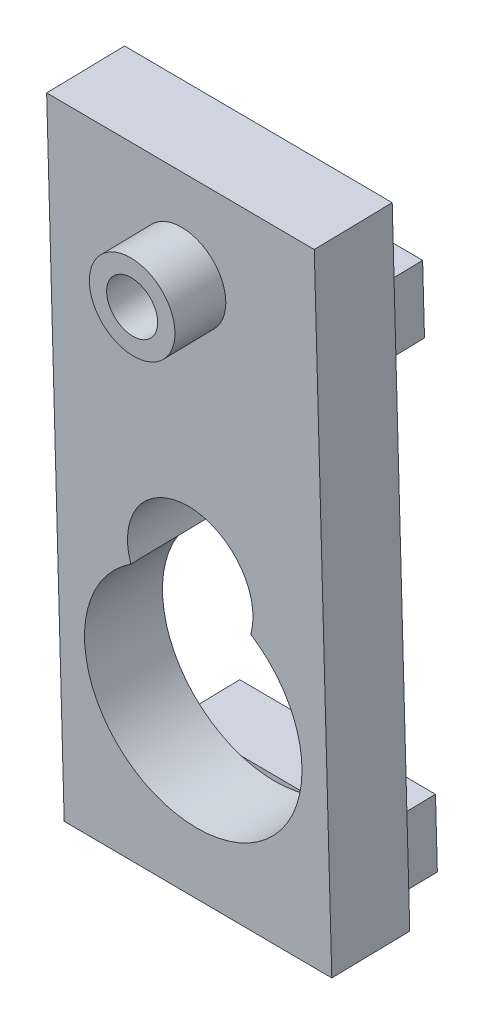
SolidWorks part; units mm, degrees
ref_plane "前视基准面" through (0, 0, 0) normal (0, 0, 1) x (1, 0, 0)
ref_plane "上视基准面" through (0, 0, 0) normal (0, 1, 0) x (1, 0, 0)
ref_plane "右视基准面" through (0, 0, 0) normal (1, 0, 0) x (0, 0, -1)
other "Configuration Table"
sketch "草图1" plane through (-0.7359, -2.9845, 108.8258) normal (-0.0068, -0.0274, 0.9996) x (1, -0.0002, 0.0068)
  line L0 (-20.1179, -7.5053) -> (-4.1179, -7.5053)
  line L1 (-4.1179, -7.5053) -> (-4.1179, 30.4947)
  line L2 (-4.1179, 30.4947) -> (-20.1179, 30.4947)
  line L3 (-20.1179, 30.4947) -> (-20.1179, -7.5053)
  dimension "D1" = 38
  dimension "D2" = 16
  dimension "D3" = 90
extrude "凸台-拉伸1" add sketch "草图1" along normal blind 4.6
sketch "草图5" plane through (-0.7359, -2.9845, 108.8258) normal (0.0068, 0.0274, -0.9996) x (-1, 0.0002, -0.0068)
  line L1 (20.1179, 30.4947) -> (20.1179, -7.5053) construction
  arc A2 (15.7034, 8.1663) -> (8.5324, 8.1663) centre (12.1179, 9.2647) ccw
  arc A3 (8.5324, 8.1663) -> (15.7034, 8.1663) centre (12.1179, 2.7447) ccw
  dimension "D1" = 8
extrude "切除-拉伸3" cut sketch "草图5" against normal up to next
sketch "草图6" plane through (-0.7359, -2.9845, 108.8258) normal (0.0068, 0.0274, -0.9996) x (-1, 0.0002, -0.0068)
  line L0 (6.2679, 20.3447) -> (6.2679, 24.3947)
  line L1 (6.2679, 24.3947) -> (17.9679, 24.3947)
  line L2 (17.9679, 24.3947) -> (17.9679, 20.3447)
  line L3 (17.5762, 23.5172) -> (17.9679, 20.3447) construction
  line L4 (17.9679, 20.3447) -> (6.2679, 20.3447)
  line L5 (7.2679, -3.4553) -> (17.9679, -3.4553)
  line L6 (17.9679, -3.4553) -> (17.9679, -7.5053)
  line L7 (20.1179, -7.5053) -> (4.1179, -7.5053) construction
  line L8 (17.9679, -7.5053) -> (6.2679, -7.5053)
  line L9 (6.2679, -7.5053) -> (6.2679, -3.4553)
  line L10 (6.2679, -3.4553) -> (7.2679, -3.4553)
  line L11 (6.2679, -2.4553) -> (6.2679, -3.4553) construction
  circle A0 centre (12.1179, 21.9447) radius 1
  circle A1 centre (12.1179, -5.0553) radius 1
extrude "凸台-拉伸2" add sketch "草图6" along normal up to surface (3.75 mm away)
sketch "草图9" plane through (-0.767, -3.1106, 113.424) normal (-0.0068, -0.0274, 0.9996) x (1, -0.0002, 0.0068)
  line L1 (-12.1179, 2.7447) -> (-12.1179, 25.0047) construction
  circle A0 centre (-12.1179, 25.0047) radius 1.525
  circle A3 centre (-12.1179, 25.0047) radius 2.56
  dimension "D1" = 3.05
  dimension "D2" = 5.12
  dimension "D3" = 22.26
extrude "凸台-拉伸3" add sketch "草图9" along normal blind 3
sketch "草图10" plane through (-0.767, -3.1106, 113.424) normal (-0.0068, -0.0274, 0.9996) x (1, -0.0002, 0.0068)
  circle A0 centre (-12.1179, 25.0047) radius 1.45
  dimension "D1" = 2.9
extrude "切除-拉伸5" cut sketch "草图10" against normal blind 2.5
